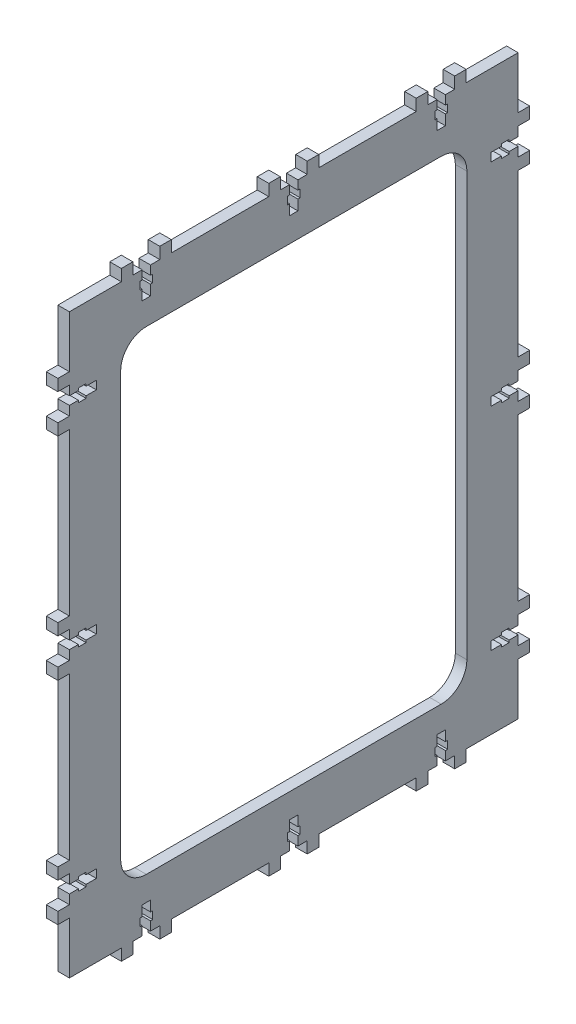
SolidWorks part; units mm, degrees
ref_plane "Front Plane" through (0, 0, 0) normal (0, 0, 1) x (1, 0, 0)
ref_plane "Top Plane" through (0, 0, 0) normal (0, 1, 0) x (1, 0, 0)
ref_plane "Right Plane" through (0, 0, 0) normal (1, 0, 0) x (0, 0, -1)
sketch "Sketch1" plane through (0, 0, 0) normal (1, 0, 0) x (0, 0, -1)
  line L0 (0, 0) -> (0, 185.0898) construction
  line L1 (-175, -225) -> (175, -225)
  line L2 (-175, -225) -> (-175, 225)
  line L3 (-175, 225) -> (175, 225)
  line L4 (175, -225) -> (175, 225)
  line L5 (-175, -225) -> (175, 225) construction
  line L6 (-175, 225) -> (175, -225) construction
  line L7 (0, 0) -> (115.6037, 0) construction
  line L9 (-115, -185) -> (115, -185)
  line L10 (-135, -165) -> (-135, 165)
  line L11 (-115, 185) -> (115, 185)
  line L12 (135, -165) -> (135, 165)
  line L13 (-135, -185) -> (135, 185) construction
  line L14 (-135, 185) -> (135, -185) construction
  arc A0 (-115, -185) -> (-135, -165) centre (-115, -165) cw
  arc A1 (135, -165) -> (115, -185) centre (115, -165) cw
  arc A2 (135, 165) -> (115, 185) centre (115, 165) ccw
  arc A3 (-115, 185) -> (-135, 165) centre (-115, 165) ccw
  point P0 (0, 0)
  line B0 (-19.5, -225) -> (-19.5, -234)
  line B1 (-19.5, -234) -> (-10.5, -234)
  line B2 (-10.5, -234) -> (-10.5, -225)
  line B3 (-10.5, -225) -> (-3.25, -225)
  line B4 (-3.25, -225) -> (-3.25, -218)
  line B5 (-3.25, -218) -> (-4.975, -218)
  line B6 (-4.975, -218) -> (-4.975, -212)
  line B7 (-4.975, -212) -> (-3.25, -212)
  line B8 (-3.25, -212) -> (-3.25, -204)
  line B9 (-3.25, -204) -> (3.25, -204)
  line B10 (0, -204) -> (0, -225) construction
  line B11 (3.25, -212) -> (3.25, -204)
  line B12 (4.975, -212) -> (3.25, -212)
  line B13 (4.975, -218) -> (4.975, -212)
  line B14 (3.25, -218) -> (4.975, -218)
  line B15 (3.25, -225) -> (3.25, -218)
  line B16 (10.5, -225) -> (3.25, -225)
  line B17 (10.5, -234) -> (10.5, -225)
  line B18 (19.5, -234) -> (10.5, -234)
  line B19 (19.5, -225) -> (19.5, -234)
  line B20 (175, -19.5) -> (184, -19.5)
  line B21 (184, -19.5) -> (184, -10.5)
  line B22 (184, -10.5) -> (175, -10.5)
  line B23 (175, -10.5) -> (175, -3.25)
  line B24 (175, -3.25) -> (168, -3.25)
  line B25 (168, -3.25) -> (168, -4.975)
  line B26 (168, -4.975) -> (162, -4.975)
  line B27 (162, -4.975) -> (162, -3.25)
  line B28 (162, -3.25) -> (154, -3.25)
  line B29 (154, -3.25) -> (154, 3.25)
  line B30 (154, 0) -> (175, 0) construction
  line B31 (162, 3.25) -> (154, 3.25)
  line B32 (162, 4.975) -> (162, 3.25)
  line B33 (168, 4.975) -> (162, 4.975)
  line B34 (168, 3.25) -> (168, 4.975)
  line B35 (175, 3.25) -> (168, 3.25)
  line B36 (175, 10.5) -> (175, 3.25)
  line B37 (184, 10.5) -> (175, 10.5)
  line B38 (184, 19.5) -> (184, 10.5)
  line B39 (175, 19.5) -> (184, 19.5)
  line B40 (95.5, -225) -> (95.5, -234)
  line B41 (95.5, -234) -> (104.5, -234)
  line B42 (104.5, -234) -> (104.5, -225)
  line B43 (104.5, -225) -> (111.75, -225)
  line B44 (111.75, -225) -> (111.75, -218)
  line B45 (111.75, -218) -> (110.025, -218)
  line B46 (110.025, -218) -> (110.025, -212)
  line B47 (110.025, -212) -> (111.75, -212)
  line B48 (111.75, -212) -> (111.75, -204)
  line B49 (111.75, -204) -> (118.25, -204)
  line B50 (115, -204) -> (115, -225) construction
  line B51 (118.25, -212) -> (118.25, -204)
  line B52 (119.975, -212) -> (118.25, -212)
  line B53 (119.975, -218) -> (119.975, -212)
  line B54 (118.25, -218) -> (119.975, -218)
  line B55 (118.25, -225) -> (118.25, -218)
  line B56 (125.5, -225) -> (118.25, -225)
  line B57 (125.5, -234) -> (125.5, -225)
  line B58 (134.5, -234) -> (125.5, -234)
  line B59 (134.5, -225) -> (134.5, -234)
  line B60 (175, -184.5) -> (184, -184.5)
  line B61 (184, -184.5) -> (184, -175.5)
  line B62 (184, -175.5) -> (175, -175.5)
  line B63 (175, -175.5) -> (175, -168.25)
  line B64 (175, -168.25) -> (168, -168.25)
  line B65 (168, -168.25) -> (168, -169.975)
  line B66 (168, -169.975) -> (162, -169.975)
  line B67 (162, -169.975) -> (162, -168.25)
  line B68 (162, -168.25) -> (154, -168.25)
  line B69 (154, -168.25) -> (154, -161.75)
  line B70 (154, -165) -> (175, -165) construction
  line B71 (162, -161.75) -> (154, -161.75)
  line B72 (162, -160.025) -> (162, -161.75)
  line B73 (168, -160.025) -> (162, -160.025)
  line B74 (168, -161.75) -> (168, -160.025)
  line B75 (175, -161.75) -> (168, -161.75)
  line B76 (175, -154.5) -> (175, -161.75)
  line B77 (184, -154.5) -> (175, -154.5)
  line B78 (184, -145.5) -> (184, -154.5)
  line B79 (175, -145.5) -> (184, -145.5)
  line B80 (-95.5, -225) -> (-95.5, -234)
  line B81 (-95.5, -234) -> (-104.5, -234)
  line B82 (-104.5, -234) -> (-104.5, -225)
  line B83 (-104.5, -225) -> (-111.75, -225)
  line B84 (-111.75, -225) -> (-111.75, -218)
  line B85 (-111.75, -218) -> (-110.025, -218)
  line B86 (-110.025, -218) -> (-110.025, -212)
  line B87 (-110.025, -212) -> (-111.75, -212)
  line B88 (-111.75, -212) -> (-111.75, -204)
  line B89 (-111.75, -204) -> (-118.25, -204)
  line B90 (-115, -204) -> (-115, -225) construction
  line B91 (-118.25, -212) -> (-118.25, -204)
  line B92 (-119.975, -212) -> (-118.25, -212)
  line B93 (-119.975, -218) -> (-119.975, -212)
  line B94 (-118.25, -218) -> (-119.975, -218)
  line B95 (-118.25, -225) -> (-118.25, -218)
  line B96 (-125.5, -225) -> (-118.25, -225)
  line B97 (-125.5, -234) -> (-125.5, -225)
  line B98 (-134.5, -234) -> (-125.5, -234)
  line B99 (-134.5, -225) -> (-134.5, -234)
  line B100 (-175, -184.5) -> (-184, -184.5)
  line B101 (-184, -184.5) -> (-184, -175.5)
  line B102 (-184, -175.5) -> (-175, -175.5)
  line B103 (-175, -175.5) -> (-175, -168.25)
  line B104 (-175, -168.25) -> (-168, -168.25)
  line B105 (-168, -168.25) -> (-168, -169.975)
  line B106 (-168, -169.975) -> (-162, -169.975)
  line B107 (-162, -169.975) -> (-162, -168.25)
  line B108 (-162, -168.25) -> (-154, -168.25)
  line B109 (-154, -168.25) -> (-154, -161.75)
  line B110 (-154, -165) -> (-175, -165) construction
  line B111 (-162, -161.75) -> (-154, -161.75)
  line B112 (-162, -160.025) -> (-162, -161.75)
  line B113 (-168, -160.025) -> (-162, -160.025)
  line B114 (-168, -161.75) -> (-168, -160.025)
  line B115 (-175, -161.75) -> (-168, -161.75)
  line B116 (-175, -154.5) -> (-175, -161.75)
  line B117 (-184, -154.5) -> (-175, -154.5)
  line B118 (-184, -145.5) -> (-184, -154.5)
  line B119 (-175, -145.5) -> (-184, -145.5)
  line B120 (-175, -19.5) -> (-184, -19.5)
  line B121 (-184, -19.5) -> (-184, -10.5)
  line B122 (-184, -10.5) -> (-175, -10.5)
  line B123 (-175, -10.5) -> (-175, -3.25)
  line B124 (-175, -3.25) -> (-168, -3.25)
  line B125 (-168, -3.25) -> (-168, -4.975)
  line B126 (-168, -4.975) -> (-162, -4.975)
  line B127 (-162, -4.975) -> (-162, -3.25)
  line B128 (-162, -3.25) -> (-154, -3.25)
  line B129 (-154, -3.25) -> (-154, 3.25)
  line B130 (-154, 0) -> (-175, 0) construction
  line B131 (-162, 3.25) -> (-154, 3.25)
  line B132 (-162, 4.975) -> (-162, 3.25)
  line B133 (-168, 4.975) -> (-162, 4.975)
  line B134 (-168, 3.25) -> (-168, 4.975)
  line B135 (-175, 3.25) -> (-168, 3.25)
  line B136 (-175, 10.5) -> (-175, 3.25)
  line B137 (-184, 10.5) -> (-175, 10.5)
  line B138 (-184, 19.5) -> (-184, 10.5)
  line B139 (-175, 19.5) -> (-184, 19.5)
  line B140 (-175, 184.5) -> (-184, 184.5)
  line B141 (-184, 184.5) -> (-184, 175.5)
  line B142 (-184, 175.5) -> (-175, 175.5)
  line B143 (-175, 175.5) -> (-175, 168.25)
  line B144 (-175, 168.25) -> (-168, 168.25)
  line B145 (-168, 168.25) -> (-168, 169.975)
  line B146 (-168, 169.975) -> (-162, 169.975)
  line B147 (-162, 169.975) -> (-162, 168.25)
  line B148 (-162, 168.25) -> (-154, 168.25)
  line B149 (-154, 168.25) -> (-154, 161.75)
  line B150 (-154, 165) -> (-175, 165) construction
  line B151 (-162, 161.75) -> (-154, 161.75)
  line B152 (-162, 160.025) -> (-162, 161.75)
  line B153 (-168, 160.025) -> (-162, 160.025)
  line B154 (-168, 161.75) -> (-168, 160.025)
  line B155 (-175, 161.75) -> (-168, 161.75)
  line B156 (-175, 154.5) -> (-175, 161.75)
  line B157 (-184, 154.5) -> (-175, 154.5)
  line B158 (-184, 145.5) -> (-184, 154.5)
  line B159 (-175, 145.5) -> (-184, 145.5)
  line B160 (95.5, 225) -> (95.5, 234)
  line B161 (95.5, 234) -> (104.5, 234)
  line B162 (104.5, 234) -> (104.5, 225)
  line B163 (104.5, 225) -> (111.75, 225)
  line B164 (111.75, 225) -> (111.75, 218)
  line B165 (111.75, 218) -> (110.025, 218)
  line B166 (110.025, 218) -> (110.025, 212)
  line B167 (110.025, 212) -> (111.75, 212)
  line B168 (111.75, 212) -> (111.75, 204)
  line B169 (111.75, 204) -> (118.25, 204)
  line B170 (115, 204) -> (115, 225) construction
  line B171 (118.25, 212) -> (118.25, 204)
  line B172 (119.975, 212) -> (118.25, 212)
  line B173 (119.975, 218) -> (119.975, 212)
  line B174 (118.25, 218) -> (119.975, 218)
  line B175 (118.25, 225) -> (118.25, 218)
  line B176 (125.5, 225) -> (118.25, 225)
  line B177 (125.5, 234) -> (125.5, 225)
  line B178 (134.5, 234) -> (125.5, 234)
  line B179 (134.5, 225) -> (134.5, 234)
  line B180 (-19.5, 225) -> (-19.5, 234)
  line B181 (-19.5, 234) -> (-10.5, 234)
  line B182 (-10.5, 234) -> (-10.5, 225)
  line B183 (-10.5, 225) -> (-3.25, 225)
  line B184 (-3.25, 225) -> (-3.25, 218)
  line B185 (-3.25, 218) -> (-4.975, 218)
  line B186 (-4.975, 218) -> (-4.975, 212)
  line B187 (-4.975, 212) -> (-3.25, 212)
  line B188 (-3.25, 212) -> (-3.25, 204)
  line B189 (-3.25, 204) -> (3.25, 204)
  line B190 (0, 204) -> (0, 225) construction
  line B191 (3.25, 212) -> (3.25, 204)
  line B192 (4.975, 212) -> (3.25, 212)
  line B193 (4.975, 218) -> (4.975, 212)
  line B194 (3.25, 218) -> (4.975, 218)
  line B195 (3.25, 225) -> (3.25, 218)
  line B196 (10.5, 225) -> (3.25, 225)
  line B197 (10.5, 234) -> (10.5, 225)
  line B198 (19.5, 234) -> (10.5, 234)
  line B199 (19.5, 225) -> (19.5, 234)
  line B200 (-95.5, 225) -> (-95.5, 234)
  line B201 (-95.5, 234) -> (-104.5, 234)
  line B202 (-104.5, 234) -> (-104.5, 225)
  line B203 (-104.5, 225) -> (-111.75, 225)
  line B204 (-111.75, 225) -> (-111.75, 218)
  line B205 (-111.75, 218) -> (-110.025, 218)
  line B206 (-110.025, 218) -> (-110.025, 212)
  line B207 (-110.025, 212) -> (-111.75, 212)
  line B208 (-111.75, 212) -> (-111.75, 204)
  line B209 (-111.75, 204) -> (-118.25, 204)
  line B210 (-115, 204) -> (-115, 225) construction
  line B211 (-118.25, 212) -> (-118.25, 204)
  line B212 (-119.975, 212) -> (-118.25, 212)
  line B213 (-119.975, 218) -> (-119.975, 212)
  line B214 (-118.25, 218) -> (-119.975, 218)
  line B215 (-118.25, 225) -> (-118.25, 218)
  line B216 (-125.5, 225) -> (-118.25, 225)
  line B217 (-125.5, 234) -> (-125.5, 225)
  line B218 (-134.5, 234) -> (-125.5, 234)
  line B219 (-134.5, 225) -> (-134.5, 234)
  line B220 (175, 184.5) -> (184, 184.5)
  line B221 (184, 184.5) -> (184, 175.5)
  line B222 (184, 175.5) -> (175, 175.5)
  line B223 (175, 175.5) -> (175, 168.25)
  line B224 (175, 168.25) -> (168, 168.25)
  line B225 (168, 168.25) -> (168, 169.975)
  line B226 (168, 169.975) -> (162, 169.975)
  line B227 (162, 169.975) -> (162, 168.25)
  line B228 (162, 168.25) -> (154, 168.25)
  line B229 (154, 168.25) -> (154, 161.75)
  line B230 (154, 165) -> (175, 165) construction
  line B231 (162, 161.75) -> (154, 161.75)
  line B232 (162, 160.025) -> (162, 161.75)
  line B233 (168, 160.025) -> (162, 160.025)
  line B234 (168, 161.75) -> (168, 160.025)
  line B235 (175, 161.75) -> (168, 161.75)
  line B236 (175, 154.5) -> (175, 161.75)
  line B237 (184, 154.5) -> (175, 154.5)
  line B238 (184, 145.5) -> (184, 154.5)
  line B239 (175, 145.5) -> (184, 145.5)
  dimension "D7" = 20
  dimension "D1" = 450
  dimension "D2" = 350
  dimension "D3" = 60
  dimension "D4" = 60
  dimension "D5" = 40
  dimension "D6" = 40
sketch_block_instance "Plot_9mm_M6_bois-1"
sketch_block "Plot_9mm_M6_bois" parameters "D1"=9, "D2"=9, "D3"=16, "D4"=30, "D5"=9.95, "D6"=6.5, "D7"=6, "D8"=8
sketch_block_instance "Plot_9mm_M6_bois-2"
sketch_block_instance "Plot_9mm_M6_bois-4"
sketch_block_instance "Plot_9mm_M6_bois-5"
sketch_block_instance "Plot_9mm_M6_bois-6"
sketch_block_instance "Plot_9mm_M6_bois-7"
sketch_block_instance "Plot_9mm_M6_bois-8"
sketch_block_instance "Plot_9mm_M6_bois-9"
sketch_block_instance "Plot_9mm_M6_bois-10"
sketch_block_instance "Plot_9mm_M6_bois-11"
sketch_block_instance "Plot_9mm_M6_bois-12"
sketch_block_instance "Plot_9mm_M6_bois-13"
extrude "Boss-Extrude1" add sketch "Sketch1" along normal blind 9 contours L4 B235 B234 B233 B232 B231 B229 B228 B227 B226 B225 B224 L3 B175 B174 B173 B172 B171 B169 B168 B167 B166 B165 B164 B195 B194 B193 B192 B191 B189 B188 B187 B186 B185 B184 | B162 B161 B160 L3 | L3 B179 B178 B177 | B222 B221 B220 L4 | L4 B239 B238 B237 | L3 B199 B198 B197 | B182 B181 B180 L3 | B219 L3 B217 B218 | B201 B202 L3 B200 | B141 B142 L2 B140 | B159 L2 B157 B158 | B122 B121 B120 L2 | L2 B139 B138 B137 | L2 B119 B118 B117 | B102 B101 B100 L2 | L1 B99 B98 B97 | B82 B81 B80 L1 | B1 B2 L1 B0 | B19 L1 B17 B18 | B41 B42 L1 B40 | B59 L1 B57 B58 | B61 B62 L4 B60 | B79 L4 B77 B78 | B39 L4 B37 B38 | B21 B22 L4 B20
